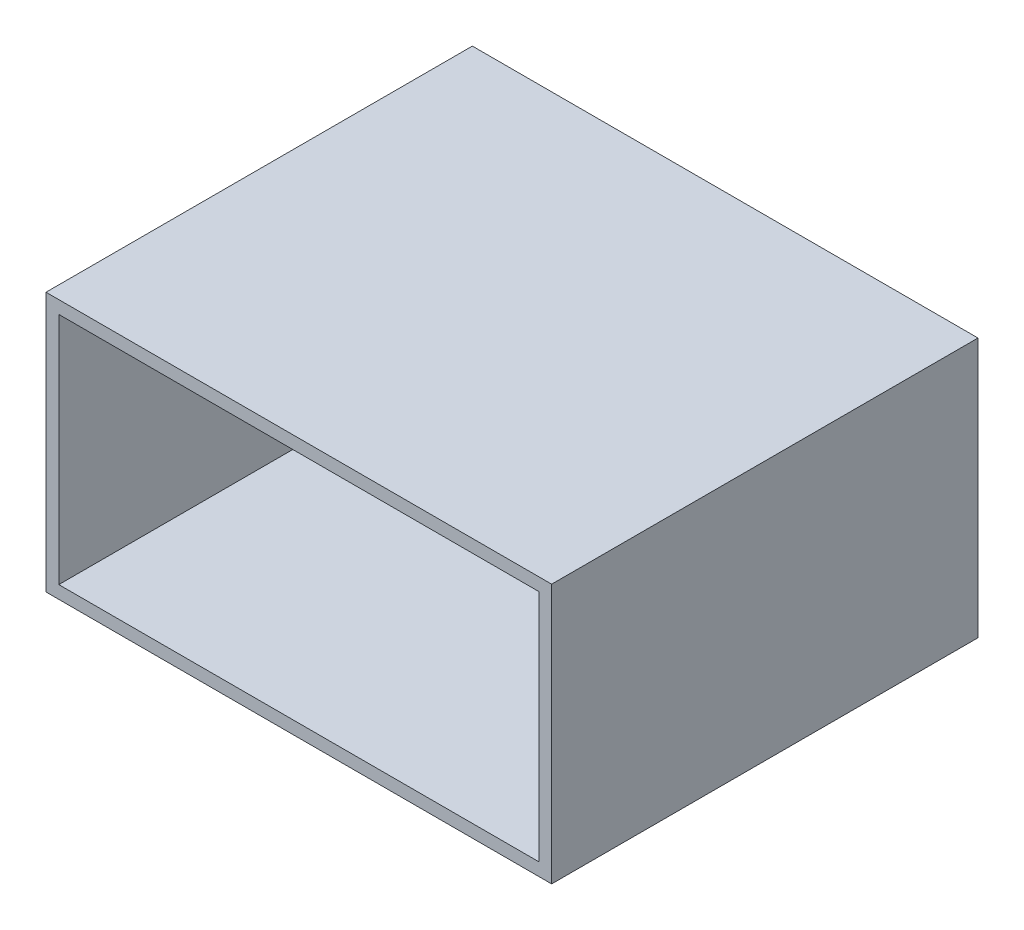
SolidWorks part; units mm, degrees
ref_plane "Front Plane" through (0, 0, 0) normal (0, 0, 1) x (1, 0, 0)
ref_plane "Top Plane" through (0, 0, 0) normal (0, 1, 0) x (1, 0, 0)
ref_plane "Right Plane" through (0, 0, 0) normal (1, 0, 0) x (0, 0, -1)
sketch "Sketch1" plane through (0, 0, 0) normal (0, 0, 1) x (1, 0, 0)
  line L1 (0, 0) -> (394.9267, 0)
  line L2 (0, 0) -> (0, 202.7697)
  line L3 (0, 202.7697) -> (394.9267, 202.7697)
  line L4 (394.9267, 0) -> (394.9267, 202.7697)
extrude "Boss-Extrude1" add sketch "Sketch1" along normal blind 333
shell "Shell5" thickness 10
ref_plane "Plane2" through (0, 0, 166.5) normal (0, 0, 1) x (1, 0, 0)
sketch "Sketch18" plane through (0, 0, 166.5) normal (0, 0, 1) x (1, 0, 0)
  line L0 (10, 128.3559) -> (81.8144, 128.3559)
  line L1 (10, 192.7697) -> (10, 10) construction
  line L2 (81.8144, 57.9602) -> (10, 57.9602)
  line L3 (10, 192.7697) -> (10, 10) construction
  line L4 (10, 57.9602) -> (10, 128.3559)
  arc A0 (81.8144, 128.3559) -> (81.8144, 57.9602) centre (81.8144, 93.1581) cw
extrude "Boss-Extrude2" add sketch "Sketch18" along normal mid plane 14
sketch "Sketch19" plane through (0, 0, 173.5) normal (0, 0, 1) x (1, 0, 0)
  circle A0 centre (81.8144, 93.1581) radius 24.923
  arc A1 (81.8144, 57.9602) -> (81.8144, 128.3559) centre (81.8144, 93.1581) ccw construction
extrude "Cut-Extrude1" cut sketch "Sketch19" against normal blind 14
sketch "Sketch22" plane through (0, 0, 166.5) normal (0, 0, 1) x (1, 0, 0)
  line L0 (384.9267, 128.3559) -> (291.109, 128.3559)
  line L1 (384.9267, 10) -> (384.9267, 192.7697) construction
  line L2 (291.109, 59.382) -> (384.9267, 59.382)
  line L3 (384.9267, 59.382) -> (384.9267, 128.3559)
  arc A0 (291.109, 128.3559) -> (291.109, 59.382) centre (291.109, 93.869) ccw
extrude "Boss-Extrude3" add sketch "Sketch22" along normal mid plane 14
sketch "Sketch23" plane through (0, 0, 173.5) normal (0, 0, 1) x (1, 0, 0)
  circle A0 centre (291.109, 93.869) radius 24.923
  circle A1 centre (81.8144, 93.1581) radius 24.923 construction
  arc A2 (291.109, 128.3559) -> (291.109, 59.382) centre (291.109, 93.869) ccw construction
extrude "Cut-Extrude2" cut sketch "Sketch23" against normal blind 14
sketch "Sketch24" plane through (0, 202.7697, 0) normal (0, 1, 0) x (1, 0, 0)
  line L0 (394.9267, 0) -> (0, 0) construction
  line L1 (5.2144, 0) -> (387.5089, 0)
  line L2 (5.2144, 0) -> (5.2144, -21.0738)
  line L3 (5.2144, -21.0738) -> (387.5089, -21.0738)
  line L4 (387.5089, 0) -> (387.5089, -21.0738)
